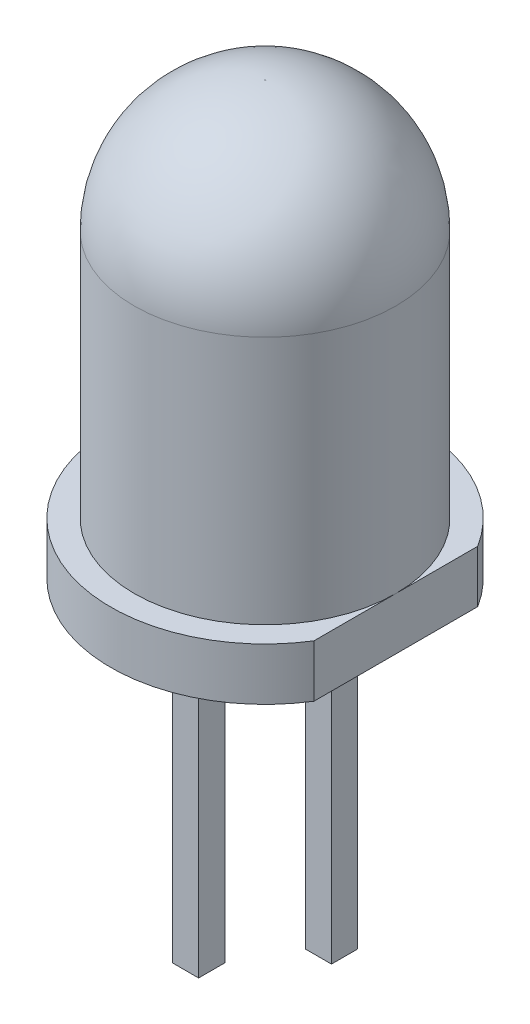
SolidWorks part; units mm, degrees
ref_plane "Alzado" through (0, 0, 0) normal (0, 0, 1) x (1, 0, 0)
ref_plane "Planta" through (0, 0, 0) normal (0, 1, 0) x (1, 0, 0)
ref_plane "Vista lateral" through (0, 0, 0) normal (1, 0, 0) x (0, 0, -1)
sketch "Croquis1" plane through (0, 0, 0) normal (0, 1, 0) x (1, 0, 0)
  circle A0 centre (0, 0) radius 2.95
  dimension "D1" = 5.9
extrude "Base" add sketch "Croquis1" along normal blind 1
sketch "Croquis2" plane through (0, 1, 0) normal (0, 1, 0) x (1, 0, 0)
  circle A0 centre (0, 0) radius 2.5
  dimension "D1" = 5
extrude "Cuerpo del LED" add sketch "Croquis2" along normal blind 7.25
sketch "Croquis3" plane through (0, 0, 0) normal (0, -1, 0) x (1, 0, 0)
  line L0 (-1.2701, 0) -> (0, 0) construction
  line L1 (0, 0) -> (1.2702, 0) construction
  line L2 (-1.5201, -0.25) -> (-1.0201, 0.25) construction
  line L3 (-1.5201, -0.25) -> (-1.0201, -0.25)
  line L4 (-1.5201, -0.25) -> (-1.5201, 0.25)
  line L5 (-1.5201, 0.25) -> (-1.0201, 0.25)
  line L6 (-1.0201, -0.25) -> (-1.0201, 0.25)
  line L7 (1.0202, -0.25) -> (1.5202, 0.25) construction
  line L8 (1.0202, -0.25) -> (1.5202, -0.25)
  line L9 (1.0202, -0.25) -> (1.0202, 0.25)
  line L10 (1.0202, 0.25) -> (1.5202, 0.25)
  line L11 (1.5202, -0.25) -> (1.5202, 0.25)
  dimension "D1" = 0.5
  dimension "D2" = 0.5
  dimension "D3" = 0.5
  dimension "D4" = 0.5
extrude "Pines" add sketch "Croquis3" along normal blind 7 from vertex at 0 starting at point (1.0202, 0, 0.25)
sketch "Croquis4" plane through (0, -7, 0) normal (0, -1, 0) x (1, 0, 0)
  line L4 (1.0202, 0.25) -> (1.0202, -0.25)
  line L5 (1.0202, -0.25) -> (1.5202, -0.25)
  line L6 (1.5202, -0.25) -> (1.5202, 0.25)
  line L7 (1.5202, 0.25) -> (1.0202, 0.25)
  line L8 (1.0202, 0.25) -> (1.0202, -0.25)
  line L9 (1.0202, -0.25) -> (1.5202, -0.25)
  line L10 (1.5202, -0.25) -> (1.5202, 0.25)
  line L11 (1.5202, 0.25) -> (1.0202, 0.25)
  dimension "D1" = 0
extrude "Corte a Catodo" cut sketch "Croquis4" against normal blind 1.5
fillet "Redondeo a Anodo" radius 0.5 4 edges at (-1.5201, 0, 0) (-1.2701, 0, -0.25) (-1.0201, 0, 0) (-1.2701, 0, 0.25)
fillet "Redondeo a Catodo" radius 0.5 4 edges at (1.0202, 0, 0) (1.2702, 0, -0.25) (1.5202, 0, 0) (1.2702, 0, 0.25)
sketch "Croquis6" plane through (0, 1, 0) normal (0, 1, 0) x (1, 0, 0)
  line L0 (2.95, 0) -> (2.5, 0) construction
  line L1 (2.5, 2.7304) -> (2.5, -3.2696)
  line L2 (2.5, -3.2696) -> (3.5, -3.2696)
  line L3 (3.5, -3.2696) -> (3.5, 2.7304)
  line L4 (3.5, 2.7304) -> (2.5, 2.7304)
  circle A0 centre (0, 0) radius 2.95 construction
  circle A1 centre (0, 0) radius 2.5 construction
  dimension "D1" = 6
  dimension "D2" = 1
extrude "Ranura" cut sketch "Croquis6" against normal up to surface (1 mm away) up to face at (1.2702, 0, 0)
fillet "Punta del Led" radius 2.49 1 edges at (0, 8.25, 2.5)
